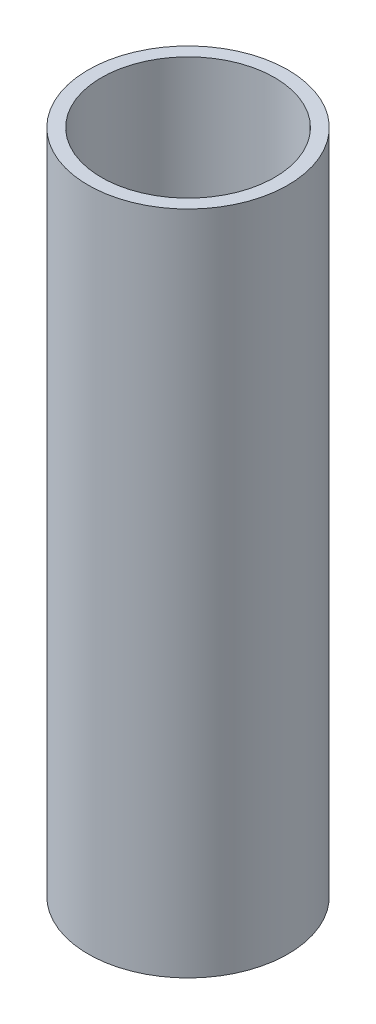
SolidWorks part; units mm, degrees
ref_plane "Спереди" through (0, 0, 0) normal (0, 0, 1) x (1, 0, 0)
ref_plane "Сверху" through (0, 0, 0) normal (0, 1, 0) x (1, 0, 0)
ref_plane "Справа" through (0, 0, 0) normal (1, 0, 0) x (0, 0, -1)
sketch "Эскиз1" plane through (0, 0, 0) normal (0, 1, 0) x (1, 0, 0)
  circle A0 centre (0, 0) radius 13
  circle A1 centre (0, 0) radius 15
  dimension "D1" = 30
  dimension "D2" = 2
extrude "Бобышка-Вытянуть1" add sketch "Эскиз1" along normal blind 90
sketch "Эскиз2" plane through (0, 0, 0) normal (0, -1, 0) x (1, 0, 0)
  circle A0 centre (0, 0) radius 15
extrude "Бобышка-Вытянуть2" add sketch "Эскиз2" along normal blind 10
sketch "Эскиз3" plane through (0, 0, 0) normal (0, 1, 0) x (1, 0, 0)
  line L1 (2.8868, 5) -> (-2.8868, 5)
  line L2 (-2.8868, 5) -> (-5.7735, 0)
  line L3 (-5.7735, 0) -> (-2.8868, -5)
  line L4 (-2.8868, -5) -> (2.8868, -5)
  line L5 (2.8868, -5) -> (5.7735, 0)
  line L6 (5.7735, 0) -> (2.8868, 5)
  circle A0 centre (0, 0) radius 5 construction
  dimension "D1" = 10
extrude "Вырез-Вытянуть1" cut sketch "Эскиз3" against normal blind 4
sketch "Эскиз4" plane through (0, -4, 0) normal (0, 1, 0) x (1, 0, 0)
  circle A0 centre (0, 0) radius 3.25
  dimension "D1" = 6.5
extrude "Вырез-Вытянуть2" cut sketch "Эскиз4" against normal through all
